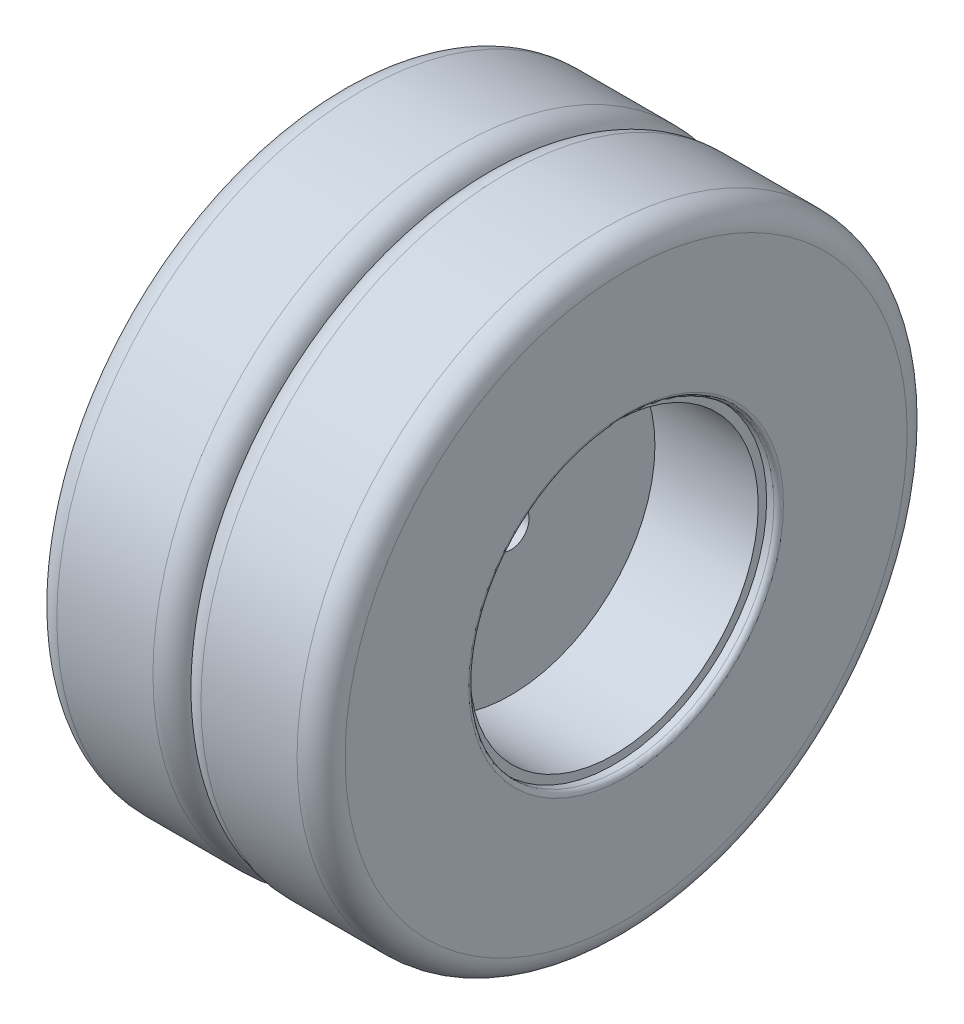
SolidWorks part; units mm, degrees
other "RHS Wheel"
other "LHS Wheel" parameters "D1"=13.6453, "D2"=113.5139, "D3"=155.7266, "D4"=155.7266
ref_plane "Front Plane" through (0, 0, 0) normal (0, 0, 1) x (1, 0, 0)
ref_plane "Top Plane" through (0, 0, 0) normal (0, 1, 0) x (1, 0, 0)
ref_plane "Right Plane" through (0, 0, 0) normal (1, 0, 0) x (0, 0, -1)
sketch "Sketch1" plane through (0, 0, 0) normal (1, 0, 0) x (0, 0, -1)
  circle A1 centre (0, 0) radius 7.625
  circle A2 centre (0, 0) radius 63.5
  dimension "D1" = 15.25
  dimension "D3" = 127
extrude "Hub Face" add sketch "Sketch1" along normal blind 7 from offset 5
sketch "Sketch2" plane through (0, 0, 0) normal (1, 0, 0) x (0, 0, -1)
  circle A0 centre (0, 0) radius 63.5
  circle A1 centre (0, 0) radius 60
  dimension "D1" = 127
  dimension "D2" = 120
extrude "Hub" add sketch "Sketch2" along normal blind 50 from offset 5
sketch "Sketch3" plane through (0, 0, 0) normal (1, 0, 0) x (0, 0, -1)
  circle A0 centre (0, 0) radius 127
  circle A1 centre (0, 0) radius 63.5
  dimension "D1" = 254
  dimension "D2" = 127
extrude "Rubber" add sketch "Sketch3" along normal blind 60
fillet "Fillet1" radius 10 2 edges at (0, 0, -127) (60, 0, -127)
fillet "Fillet2" radius 2 2 edges at (60, 0, -63.5) (0, 0, -63.5)
mirror "Mirror1" about plane through (0, 0, 0) normal (1, 0, 0) of bodies 103
equation "\"tireWidth\"= 60mm"
equation "\"tireDiameter\"= 10in"
equation "\"shaftDiameter\"= 15mm"
equation "\"hubDiameter\"= 5in"
equation "\"D1@Sketch1\"=\"shaftDiameter\" + 0.25mm"
equation "\"hubMaterialThickness\"= 7mm"
equation "\"D1@Hub Face\" = \"hubMaterialThickness\""
equation "\"D3@Sketch1\"=\"hubDiameter\""
equation "\"D1@Sketch2\"=\"hubDiameter\""
equation "\"D2@Sketch2\"=\"hubDiameter\"-\"hubMaterialThickness\""
equation "\"D1@Hub\"=\"hubWidth\""
equation "\"D1@Sketch3\"=\"tireDiameter\""
equation "\"D2@Sketch3\"=\"hubDiameter\""
equation "\"D1@Rubber\" = \"tireWidth\""
equation "\"hubWidth\"= 50mm"
equation "\"D19@Hub\"=(\"tireWidth\"-\"hubWidth\")/2"
equation "\"D19@Hub Face\"=(\"tireWidth\"-\"hubWidth\")/2"
